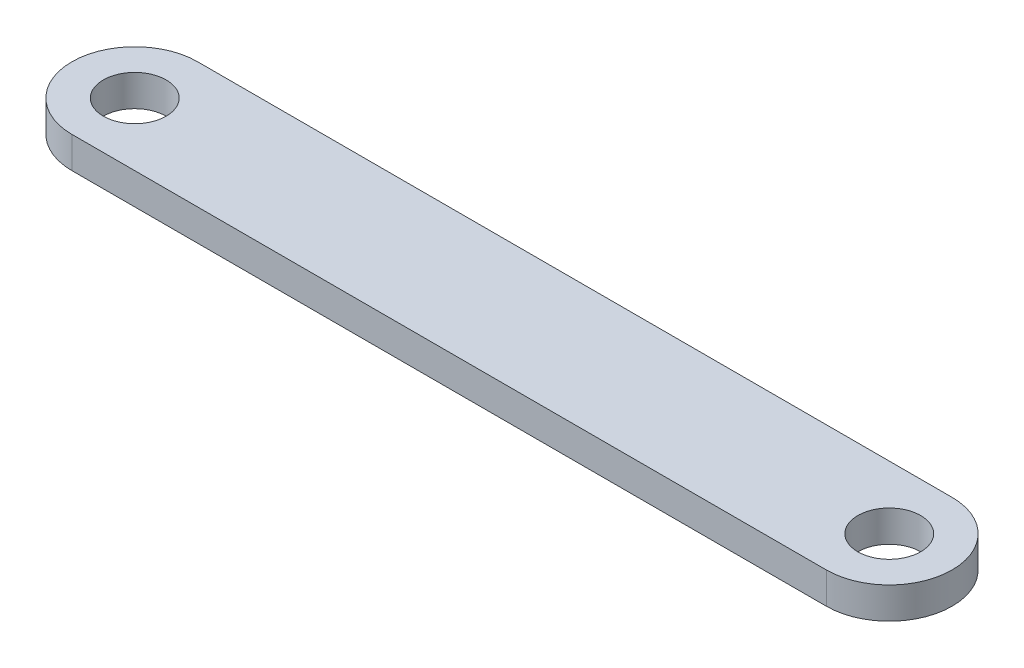
SolidWorks part; units mm, degrees
ref_plane "Ön Düzlem" through (0, 0, 0) normal (0, 0, 1) x (1, 0, 0)
ref_plane "Üst Düzlem" through (0, 0, 0) normal (0, 1, 0) x (1, 0, 0)
ref_plane "Sağ Düzlem" through (0, 0, 0) normal (1, 0, 0) x (0, 0, -1)
sketch "Sketch1" plane through (0, 0, 0) normal (0, 1, 0) x (1, 0, 0)
  line L0 (-60, 0) -> (60, 0) construction
  line L1 (-60, 10) -> (60, 10)
  line L2 (-60, -10) -> (60, -10)
  arc A0 (-60, 10) -> (-60, -10) centre (-60, 0) ccw
  arc A1 (60, -10) -> (60, 10) centre (60, 0) ccw
  circle A2 centre (-60, 0) radius 5
  circle A3 centre (60, 0) radius 5
  point P2 (0, 0)
  dimension "D1" = 10
  dimension "D3" = 10
  dimension "D4" = 10
  dimension "D2" = 120
extrude "Boss-Extrude1" add sketch "Sketch1" along normal blind 5
